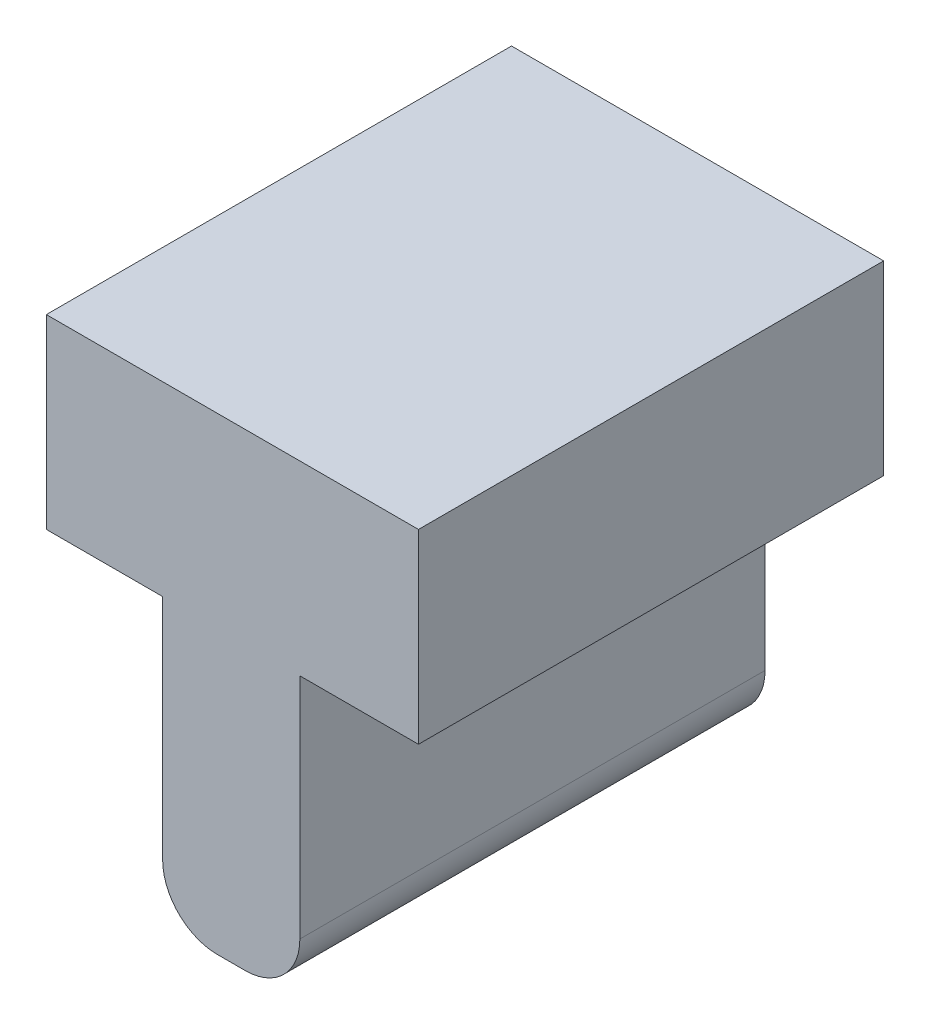
SolidWorks part; units mm, degrees
ref_plane "Front Plane" through (0, 0, 0) normal (0, 0, 1) x (1, 0, 0)
ref_plane "Top Plane" through (0, 0, 0) normal (0, 1, 0) x (1, 0, 0)
ref_plane "Right Plane" through (0, 0, 0) normal (1, 0, 0) x (0, 0, -1)
sketch "Sketch1" plane through (0, 0, 0) normal (0, 0, 1) x (1, 0, 0)
  line L1 (8, -8.075) -> (-8, -8.075) construction
  line L2 (8, -8.075) -> (8, 8.075) construction
  line L3 (8, 8.075) -> (2.9, 8.075)
  line L4 (-8, -8.075) -> (-8, 8.075) construction
  line L5 (8, -8.075) -> (-8, 8.075) construction
  line L6 (8, 8.075) -> (-8, -8.075) construction
  line L9 (-3, 8.075) -> (-8, 8.075)
  line L10 (-3, 8.075) -> (-3, -1.725)
  line L11 (-0.65, -4.075) -> (0.55, -4.075)
  line L12 (2.9, -1.725) -> (2.9, 8.075)
  line L13 (8, 8.075) -> (8, 16.075)
  line L14 (8, 16.075) -> (-8, 16.075)
  line L15 (-8, 16.075) -> (-8, 8.075)
  arc A0 (0.55, -4.075) -> (2.9, -1.725) centre (0.55, -1.725) ccw
  arc A1 (-3, -1.725) -> (-0.65, -4.075) centre (-0.65, -1.725) ccw
  point P0 (0, 0)
  dimension "D4" = 2.35
  dimension "D1" = 16
  dimension "D2" = 16.15
  dimension "D3" = 5
  dimension "D5" = 12.15
  dimension "D6" = 5.9
  dimension "D7" = 8
extrude "Boss-Extrude1" add sketch "Sketch1" against normal mid plane 20
